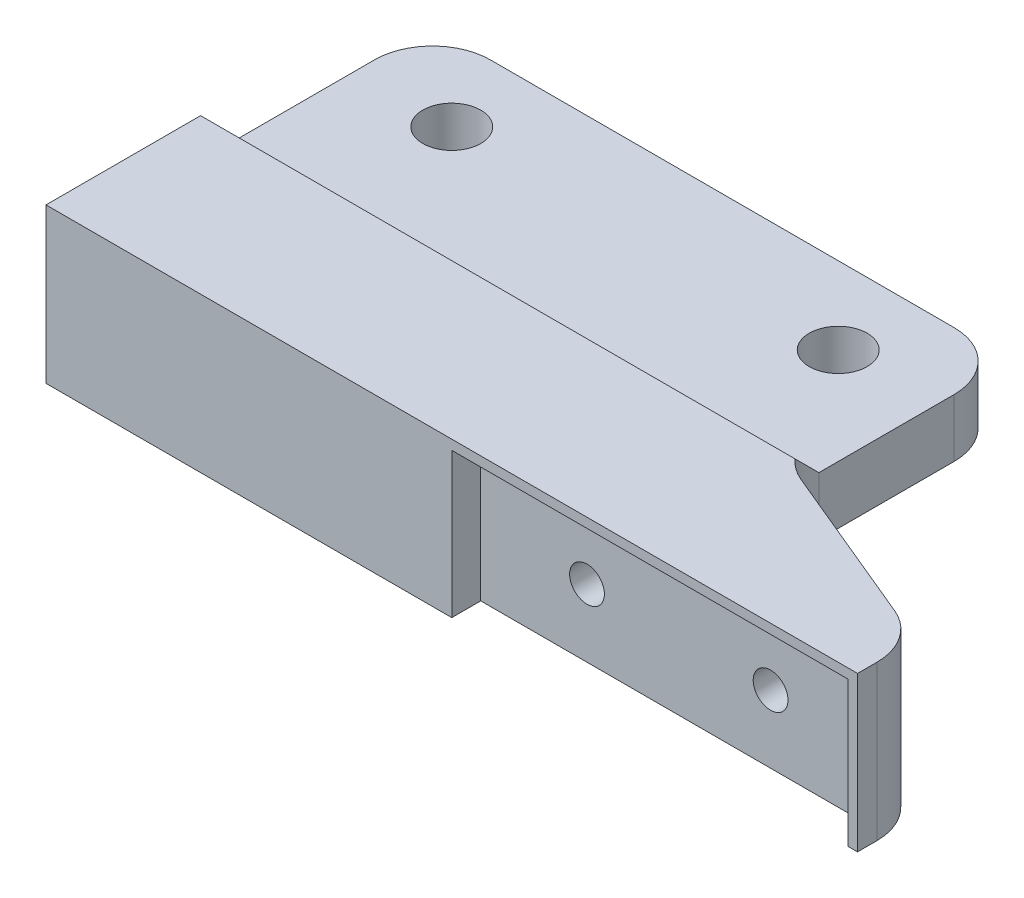
SolidWorks part; units mm, degrees
ref_plane "前视基准面" through (0, 0, 0) normal (0, 0, 1) x (1, 0, 0)
ref_plane "上视基准面" through (0, 0, 0) normal (0, 1, 0) x (1, 0, 0)
ref_plane "右视基准面" through (0, 0, 0) normal (1, 0, 0) x (0, 0, -1)
sketch "草图1" plane through (0, 0, 0) normal (0, 1, 0) x (1, 0, 0)
  line L0 (0, 0) -> (42, 0)
  line L1 (42, 0) -> (42, 3)
  line L2 (42, 3) -> (30, 8)
  line L3 (30, 8) -> (30, 20)
  line L4 (30, 20) -> (0, 20)
  line L5 (0, 20) -> (0, 0)
  line L6 (5, 16) -> (25, 16) construction
  line L7 (31.1469, 1.5) -> (40.6469, 1.5) construction
  circle A0 centre (25, 16) radius 1.5
  circle A1 centre (5, 16) radius 1.5
  dimension "D3" = 3
  dimension "D5" = 5
  dimension "D1" = 20
  dimension "D2" = 20
  dimension "D4" = 4
  dimension "D6" = 30
  dimension "D7" = 1.5
  dimension "D8" = 9.5
  dimension "D9" = 42
  dimension "D10" = 3
  dimension "D11" = 12
extrude "凸台-拉伸1" add sketch "草图1" along normal blind 8
sketch "草图2" plane through (0, 0, 0) normal (-1, 0, 0) x (0, 0, 1)
  line L0 (-20, 6) -> (-10, 6)
  line L1 (-20, 0) -> (-8, 0)
  line L2 (-20, 0) -> (-20, 3)
  line L3 (-20, 3) -> (-8, 3)
  line L4 (-8, 0) -> (-8, 3)
  line L5 (-20, 8) -> (-20, 0) construction
  line L6 (-10, 6) -> (-8, 8)
  line L7 (-20, 8) -> (0, 8) construction
  line L8 (-8, 8) -> (-20, 8)
  line L9 (-20, 8) -> (-20, 6)
  point P12 (0, 0)
  dimension "D1" = 12
  dimension "D2" = 3
  dimension "D3" = 3
  dimension "D4" = 45
extrude "切除-拉伸1" cut sketch "草图2" against normal through all
sketch "草图3" plane through (0, 0, 0) normal (0, 0, 1) x (1, 0, 0)
  line L0 (26.5, 3.5) -> (36, 3.5) construction
  line L1 (42, 8) -> (42, 0) construction
  line L2 (0, 0) -> (42, 0) construction
  circle A0 centre (26.5, 3.5) radius 0.9
  circle A1 centre (36, 3.5) radius 0.9
  dimension "D1" = 1.8
  dimension "D3" = 6
  dimension "D2" = 9.5
  dimension "D4" = 3.5
extrude "切除-拉伸2" cut sketch "草图3" against normal blind 6
sketch "草图4" plane through (0, 0, 0) normal (0, 0, 1) x (1, 0, 0)
  line L0 (0, 0) -> (42, 0) construction
  line L1 (21, 0) -> (41.5, 0)
  line L2 (21, 0) -> (21, 7.5)
  line L3 (21, 7.5) -> (41.5, 7.5)
  line L4 (41.5, 0) -> (41.5, 7.5)
  circle A0 centre (26.5, 3.5) radius 0.9 construction
  circle A1 centre (36, 3.5) radius 0.9 construction
  circle A2 centre (26.5, 3.5) radius 0.9 construction
  point P6 (38.8858, 5.1941)
  point P7 (23.0404, 4.8902)
  dimension "D1" = 5.5
  dimension "D2" = 5.5
  dimension "D3" = 4
extrude "切除-拉伸3" cut sketch "草图4" against normal blind 1.5
fillet "圆角2" radius 3 4 edges at (0, 4.5, -20) (30, 4.5, -20) (42, 4, -3) (30, 5.5, -8)
fillet "圆角3" radius 3 1 edges at (30, 1.5, -8)
